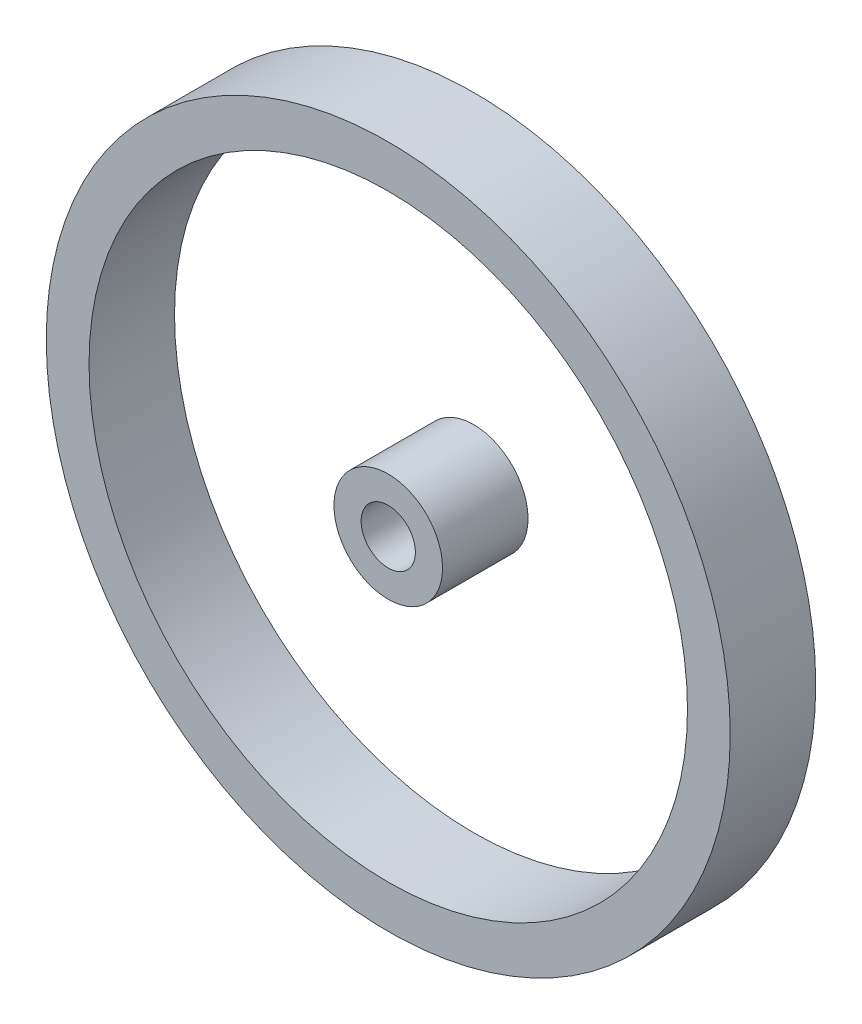
SolidWorks part; units mm, degrees
ref_plane "Front Plane" through (0, 0, 0) normal (0, 0, 1) x (1, 0, 0)
ref_plane "Top Plane" through (0, 0, 0) normal (0, 1, 0) x (1, 0, 0)
ref_plane "Right Plane" through (0, 0, 0) normal (1, 0, 0) x (0, 0, -1)
sketch "Sketch1" plane through (0, 0, 0) normal (0, 0, 1) x (1, 0, 0)
  circle A0 centre (0, 0) radius 40
  circle A1 centre (0, 0) radius 35
  circle A2 centre (0, 0) radius 3.175
  circle A3 centre (0, 0) radius 6.35
  dimension "D1" = 80
  dimension "D2" = 70
  dimension "D3" = 6.35
  dimension "D4" = 12.7
extrude "Boss-Extrude1" add sketch "Sketch1" along normal blind 10 contours A0 A1 | A3 A2
